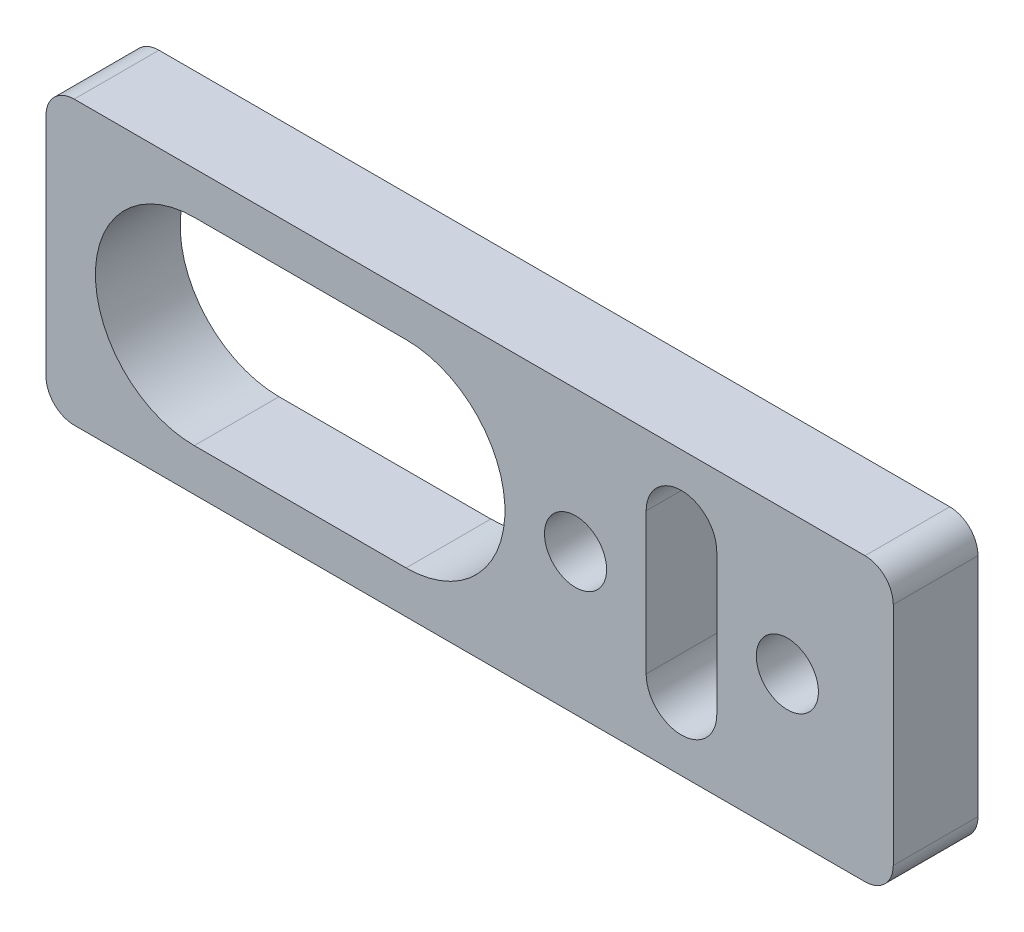
SolidWorks part; units mm, degrees
ref_plane "前视基准面" through (0, 0, 0) normal (0, 0, 1) x (1, 0, 0)
ref_plane "上视基准面" through (0, 0, 0) normal (0, 1, 0) x (1, 0, 0)
ref_plane "右视基准面" through (0, 0, 0) normal (1, 0, 0) x (0, 0, -1)
sketch "草图1" plane through (0, 0, 0) normal (0, 0, 1) x (1, 0, 0)
  line L1 (-30, -10) -> (30, -10)
  line L2 (-30, -10) -> (-30, 10)
  line L3 (-30, 10) -> (30, 10)
  line L4 (30, -10) -> (30, 10)
  line L5 (-30, -10) -> (30, 10) construction
  line L6 (-30, 10) -> (30, -10) construction
  point P0 (0, 0)
  dimension "D1" = 20
  dimension "D2" = 60
extrude "凸台-拉伸1" add sketch "草图1" along normal blind 6
fillet "圆角1" radius 2 4 edges at (30, 10, 3) (30, -10, 3) (-30, -10, 3) (-30, 10, 3)
sketch "草图2" plane through (0, 0, 6) normal (0, 0, 1) x (1, 0, 0)
  line L0 (0, 0) -> (50000, 0) construction
  line L1 (30, -8) -> (30, 8) construction
  circle A0 centre (22.5, 0) radius 2.2
  circle A1 centre (7.5, 0) radius 2.2
  dimension "D1" = 4.4
  dimension "D2" = 4.4
  dimension "D3" = 7.5
  dimension "D4" = 15
extrude "切除-拉伸1" cut sketch "草图2" against normal through all
sketch "草图3" plane through (0, 0, 6) normal (0, 0, 1) x (1, 0, 0)
  line L0 (-19.5, 0) -> (-4.5, 0) construction
  line L1 (-19.5, 7) -> (-4.5, 7)
  line L2 (-19.5, -7) -> (-4.5, -7)
  line L3 (15, -5) -> (15, 5) construction
  line L6 (12.5, -5) -> (12.5, 5)
  line L7 (17.5, -5) -> (17.5, 5)
  line L8 (7.5, 0) -> (22.5, 0) construction
  arc A0 (-19.5, 7) -> (-19.5, -7) centre (-19.5, 0) ccw
  arc A1 (-4.5, -7) -> (-4.5, 7) centre (-4.5, 0) ccw
  arc A4 (12.5, -5) -> (17.5, -5) centre (15, -5) ccw
  arc A5 (17.5, 5) -> (12.5, 5) centre (15, 5) ccw
  point P3 (-12, 0)
  point P10 (15, 0)
  dimension "D1" = 7
  dimension "D5" = 2.5
  dimension "D2" = 15
  dimension "D3" = 12
  dimension "D4" = 10
extrude "切除-拉伸2" cut sketch "草图3" against normal through all
